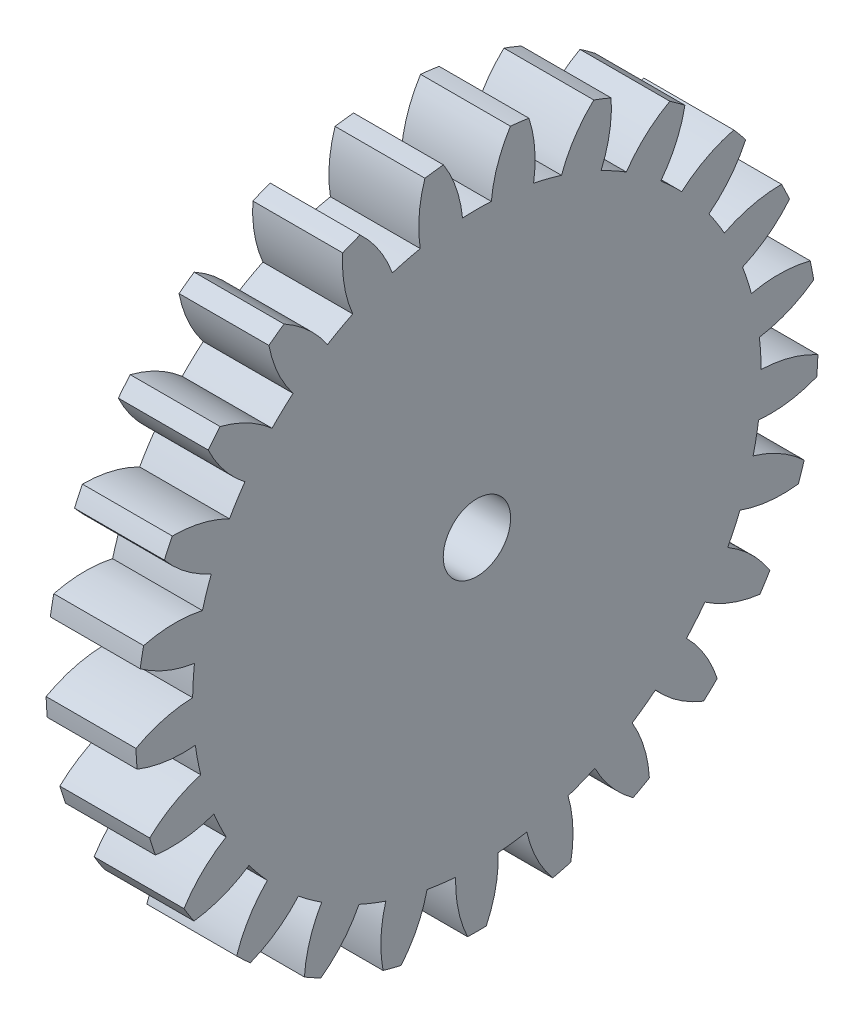
SolidWorks part; units mm, degrees
ref_plane "Plane1" through (0, 0, 0) normal (0, 0, 1) x (1, 0, 0)
ref_plane "Plane2" through (0, 0, 0) normal (0, 1, 0) x (1, 0, 0)
ref_plane "Plane3" through (0, 0, 0) normal (1, 0, 0) x (0, 0, -1)
sketch "HoldingSke" plane through (0, 0, 0) normal (0, 1, 0) x (1, 0, 0)
  line L0 (0, 0) -> (0.8056, -0.3757)
  line L1 (-15, 0) -> (100, 0) construction
  line L2 (0, 0) -> (-2.1039, 2.3779)
  line L3 (0, 0) -> (-11.863, 4.5341)
  line L4 (0, 0) -> (7.8269, 3.6497)
  line L5 (0, 0) -> (-46.8476, -17.4728)
  line L6 (0, 0) -> (-3.3159, -2.2372)
  line L7 (-2.1039, 2.3779) -> (8.6586, 51.2059)
  line L8 (-76.2, 54.61) -> (-75.7, 54.61)
  line L9 (-67.7845, 28.3722) -> (-49.3413, 33.142)
  line L10 (-76.2, 71.12) -> (104.1128, 71.12)
  line L11 (0, 0) -> (-4, 0)
  line L12 (-76.2, 101.6) -> (-76.158, 101.6)
  line L13 (24.9733, 27.94) -> (52.9518, 28.4284)
  line L14 (24.9733, 27.94) -> (24.9743, 27.94)
  line L15 (24.9733, 27.94) -> (100.4006, 29.5858)
  line L16 (-63.627, -1.125) -> (-12.827, -1.125)
  circle A0 centre (0, 0) radius 1.5
  circle A1 centre (0, 0) radius 12.6552
  circle A2 centre (0, 0) radius 37.5
  circle A3 centre (0, 0) radius 1.5
  dimension "MHD" = 25.3105
  dimension "Hub_dia" = 75
  dimension "Bore" = 3
  dimension "MBD" = 3
  dimension "Num_teeth" = 25
  dimension "Pitch" = 0.8889
  dimension "Overall_len" = 50
  dimension "Show_teeth" = 25
  dimension "Thickness" = 4
  dimension "OAL" = 50.0001
  dimension "T_dim" = 0.5
  dimension "Ap" = 14.5
  dimension "H" = 19.05
  dimension "Pitch_radius" = 180.3128
  dimension "Width" = 4
  dimension "Backlash" = 0.042
  dimension "Addendum_fac" = 1
  dimension "Dedendum_fac" = 1.25
  dimension "Clearance_fac" = 0.25
  dimension "Dedendum_add" = 0.001
  dimension "Module" = 1.125
sketch "BasProSke" plane through (0, 0, 0) normal (0, 1, 0) x (1, 0, 0)
  line L0 (-10, 0) -> (60, 0) construction
  line L1 (0, 0) -> (0, 15.1875)
  line L2 (0, 0) -> (4, 0)
  line L3 (4, 0) -> (4, 15.1875)
  line L4 (4, 15.1875) -> (0, 15.1875)
  dimension "Thickness" = 4
  dimension "Diameter" = 30.375
revolve "Base-Revolve" add sketch "BasProSke" angle 360 about L0
sketch "TooCutSke" plane through (0, 0, 0) normal (1, 0, 0) x (0, 0, -1)
  line L1 (0, 0) -> (0, 107) construction
  line L2 (0, 0) -> (-0.9565, 14.0299) construction
  line L3 (0, 0) -> (-3.5192, 27.857) construction
  line L4 (-0.9565, 14.0299) -> (-1.7596, 13.9285) construction
  arc A0 (0.641, 12.639) -> (-0.641, 12.639) centre (0, 0) ccw
  arc A1 (1.506, 15.1382) -> (-1.506, 15.1382) centre (0, 0) ccw
  circle A2 centre (0, 0) radius 14.0625 construction
  circle A3 centre (0, 0) radius 13.6146 construction
  arc A4 (-0.641, 12.639) -> (-1.506, 15.1382) centre (-6.2401, 12.1003) ccw
  arc A5 (1.506, 15.1382) -> (0.641, 12.639) centre (6.2401, 12.1003) ccw
  dimension "Root_dia" = 25.3105
  dimension "Overcut_dia" = 30.4258
  dimension "Pitch_dia" = 28.125
  dimension "Base_dia" = 27.2292
  dimension "Flank_rad" = 5.625
  dimension "Half_ang" = 7.2
  dimension "Half_CT" = 0.8095
extrude "ToothCut" cut sketch "TooCutSke" along normal through all
fillet "Breaks" [suppressed] radius 0.0225
fillet "RootFillets" [suppressed] radius 0.2823
pattern_circular "TeethCuts" count 25 every 14.4 about axis through (-10, 0, 0) along (1, 0, 0) of "ToothCut", "RootFillets", "Breaks"
sketch "HubNeaOneSke" plane through (0, 0, 0) normal (-1, 0, 0) x (0, 0, 1)
  circle A0 centre (0, 0) radius 12.6552
  dimension "Diameter" = 25.3105
extrude "HubNearOne" [suppressed] add sketch "HubNeaOneSke" along normal blind 46.0001
sketch "HubNeaBotSke" plane through (0, 0, 0) normal (-1, 0, 0) x (0, 0, 1)
  circle A0 centre (0, 0) radius 12.6552
  dimension "Diameter" = 25.3105
extrude "HubNearBoth" [suppressed] add sketch "HubNeaBotSke" along normal blind 23
ref_plane "FarPln" through (4, 0, 0) normal (1, 0, 0) x (0, 0, -1)
sketch "HubFarSke" plane through (4, 0, 0) normal (1, 0, 0) x (0, 0, -1)
  circle A0 centre (0, 0) radius 12.6552
  dimension "Diameter" = 25.3105
extrude "HubFar" [suppressed] add sketch "HubFarSke" along normal blind 23
sketch "BorSke" plane through (0, 0, 0) normal (1, 0, 0) x (0, 0, -1)
  circle A0 centre (0, 0) radius 1.5
  dimension "Diameter" = 3
extrude "Bore" cut sketch "BorSke" along normal mid plane 100.0001
sketch "KeySke" plane through (0, 0, 0) normal (1, 0, 0) x (0, 0, -1)
  line L0 (-0.6, 0) -> (-0.6, 2)
  line L1 (-0.6, 2) -> (0.6, 2)
  line L2 (0.6, 2) -> (0.6, 0)
  line L3 (0, 0) -> (0, 34) construction
  line L4 (-0.6, 0) -> (0.6, 0)
  dimension "Offset" = 2
  dimension "Width" = 1.2
extrude "Keyway" [suppressed] cut sketch "KeySke" along normal mid plane 100.0001
pattern_circular "Keyway2" [suppressed] count 2 every 90 about axis through (-10, 0, 0) along (1, 0, 0)
equation "' \"Module@HoldingSke\" = 6.35"
equation "' \"Num_teeth@HoldingSke\" = 12"
equation "' \"Ap@HoldingSke\" =  20"
equation "' \"Ap@HoldingSke\" = 20"
equation "' \"Width@HoldingSke\" = 0.5 * 25.4"
equation "' \"Hub_dia@HoldingSke\"= 1 * 25.4"
equation "' \"Hub_dia@HoldingSke\" = 1 * 25.4"
equation "' \"Overall_len@HoldingSke\" = 1.0 * 25.4"
equation "' \"Bore@HoldingSke\" = 0.75 * 25.4"
equation "' \"T_dim@HoldingSke\" = 0.1 * 25.4"
equation "' \"Width@KeySke\" = 0.25 * 25.4"
equation "' \"Show_teeth@HoldingSke\" = 13"
equation "' \"Backlash@HoldingSke\" = 0.009 * 25.4"
equation "' \"Addendum_fac@HoldingSke\" = 1.0"
equation "' \"Dedendum_fac@HoldingSke\" = 1.25"
equation "' \"Dedendum_add@HoldingSke\" = 0.00005 * 25.4"
equation "' \"Clearance_fac@HoldingSke\" = 0.25"
equation "\"Pitch@HoldingSke\" = 1 / \"Module@HoldingSke\""
equation "\"Overcut_dia@TooCutSke\" = (\"Num_teeth@HoldingSke\" + 2 * \"Addendum_fac@HoldingSke\") / \"Pitch@HoldingSke\" + 0.002 * 25.4"
equation "\"Pitch_dia@TooCutSke\" = \"Num_teeth@HoldingSke\" / \"Pitch@HoldingSke\""
equation "\"Base_dia@TooCutSke\" = \"Num_teeth@HoldingSke\" / \"Pitch@HoldingSke\" * cos((\"Ap@HoldingSke\"  * 3.14159265 / 180))"
equation "\"Root_dia@TooCutSke\" = (\"Num_teeth@HoldingSke\" + 2) / \"Pitch@HoldingSke\" - 2 * (\"Addendum_fac@HoldingSke\" + \"Dedendum_fac@HoldingSke\") / \"Pitch@HoldingSke\" - \"Dedendum_add@HoldingSke\" * 2"
equation "\"Half_ang@TooCutSke\" = 180 / \"Num_teeth@HoldingSke\""
equation "\"Half_CT@TooCutSke\" = \"Num_teeth@HoldingSke\" / \"Pitch@HoldingSke\" * sin((3.14159265 / 2 / \"Num_teeth@HoldingSke\")) / 2 - 7 * \"Backlash@HoldingSke\" / 4"
equation "\"Flank_rad@TooCutSke\" = \"Num_teeth@HoldingSke\" / \"Pitch@HoldingSke\" / 5"
equation "\"Radius@RootFillets\" = \"Clearance_fac@HoldingSke\" / \"Pitch@HoldingSke\" + \"Dedendum_add@HoldingSke\""
equation "\"Break_rad@Breaks\" = 0.02 / \"Pitch@HoldingSke\""
equation "\"Thickness@HoldingSke\" = \"Width@HoldingSke\""
equation "\"OAL@HoldingSke\" = \"Thickness@HoldingSke\""
equation "\"MHD@HoldingSke\" = (\"Num_teeth@HoldingSke\" + 2) / \"Pitch@HoldingSke\" - 2 * (\"Addendum_fac@HoldingSke\" + \"Dedendum_fac@HoldingSke\")  / \"Pitch@HoldingSke\" - \"Dedendum_add@HoldingSke\" * 2"
equation "\"MBD@HoldingSke\" = (\"Num_teeth@HoldingSke\" + 2) / \"Pitch@HoldingSke\" - 2 * (\"Addendum_fac@HoldingSke\" + \"Dedendum_fac@HoldingSke\")  / \"Pitch@HoldingSke\" - \"Dedendum_add@HoldingSke\" * 2 - 0.002 * 25.4"
equation "\"MHD@HoldingSke\" = ((sgn( \"MHD@HoldingSke\" - \"Hub_dia@HoldingSke\" )-1)*( \"MHD@HoldingSke\" - \"Hub_dia@HoldingSke\" ))/-2+ \"Hub_dia@HoldingSke\""
equation "\"MBD@HoldingSke\" = ((sgn( \"MBD@HoldingSke\" - \"Bore@HoldingSke\" )-1)*( \"MBD@HoldingSke\" - \"Bore@HoldingSke\" ))/-2+ \"Bore@HoldingSke\""
equation "\"OAL@HoldingSke\" = ((sgn( \"OAL@HoldingSke\" - \"Overall_len@HoldingSke\" )+1)*( \"OAL@HoldingSke\" - \"Overall_len@HoldingSke\" ))/2 + \"Overall_len@HoldingSke\" + 0.000002 * 25.4"
equation "\"Num_teeth@TeethCuts\" = int( \"Show_teeth@HoldingSke\" ) + 1"
equation "\"Num_teeth@TeethCuts\" = ((sgn( \"Num_teeth@TeethCuts\" - \"Num_teeth@HoldingSke\" )-1)*( \"Num_teeth@TeethCuts\" - \"Num_teeth@HoldingSke\" ))/-2+ \"Num_teeth@HoldingSke\""
equation "\"Num_teeth@TeethCuts\" = ((sgn( \"Num_teeth@TeethCuts\" - 2.0)+1)*( \"Num_teeth@TeethCuts\" - 2.0))/2 +2.0"
equation "\"Angle@TeethCuts\" = 360.0 / \"Num_teeth@HoldingSke\""
equation "\"Diameter@BasProSke\" = (\"Num_teeth@HoldingSke\" + 2 * \"Addendum_fac@HoldingSke\") / \"Pitch@HoldingSke\""
equation "\"Thickness@BasProSke\"  = \"Thickness@HoldingSke\""
equation "' \"Fillet_rad@BasProSke\" =  \"Thickness@HoldingSke\" * 0.05"
equation "' \"Fillet_rad@BasProSke\" = \"Thickness@HoldingSke\" * 0.05"
equation "\"MHD@HoldingSke\" = ((sgn( \"MHD@HoldingSke\" - \"Root_dia@TooCutSke\" )-1)*( \"MHD@HoldingSke\" - \"Root_dia@TooCutSke\" ))/-2+ \"Root_dia@TooCutSke\""
equation "\"Diameter@HubNeaOneSke\" = \"MHD@HoldingSke\""
equation "\"Length@HubNearOne\" = \"OAL@HoldingSke\" - \"Thickness@BasProSke\""
equation "\"Diameter@HubNeaBotSke\" = \"MHD@HoldingSke\""
equation "\"Length@HubNearBoth\" = ( \"OAL@HoldingSke\" - \"Thickness@BasProSke\" ) / 2.0"
equation "\"Thickness@FarPln\" = \"Thickness@BasProSke\""
equation "\"Diameter@HubFarSke\" = \"MHD@HoldingSke\""
equation "\"Length@HubFar\" = ( \"OAL@HoldingSke\" - \"Thickness@BasProSke\" ) / 2.0"
equation "\"Diameter@BorSke\" = \"MBD@HoldingSke\""
equation "\"D1@Bore\" = \"OAL@HoldingSke\" * 2.0"
equation "\"D1@Keyway\" = \"OAL@HoldingSke\" * 2.0"
equation "\"Offset@KeySke\" = \"T_dim@HoldingSke\" + \"MBD@HoldingSke\" / 2.0"
